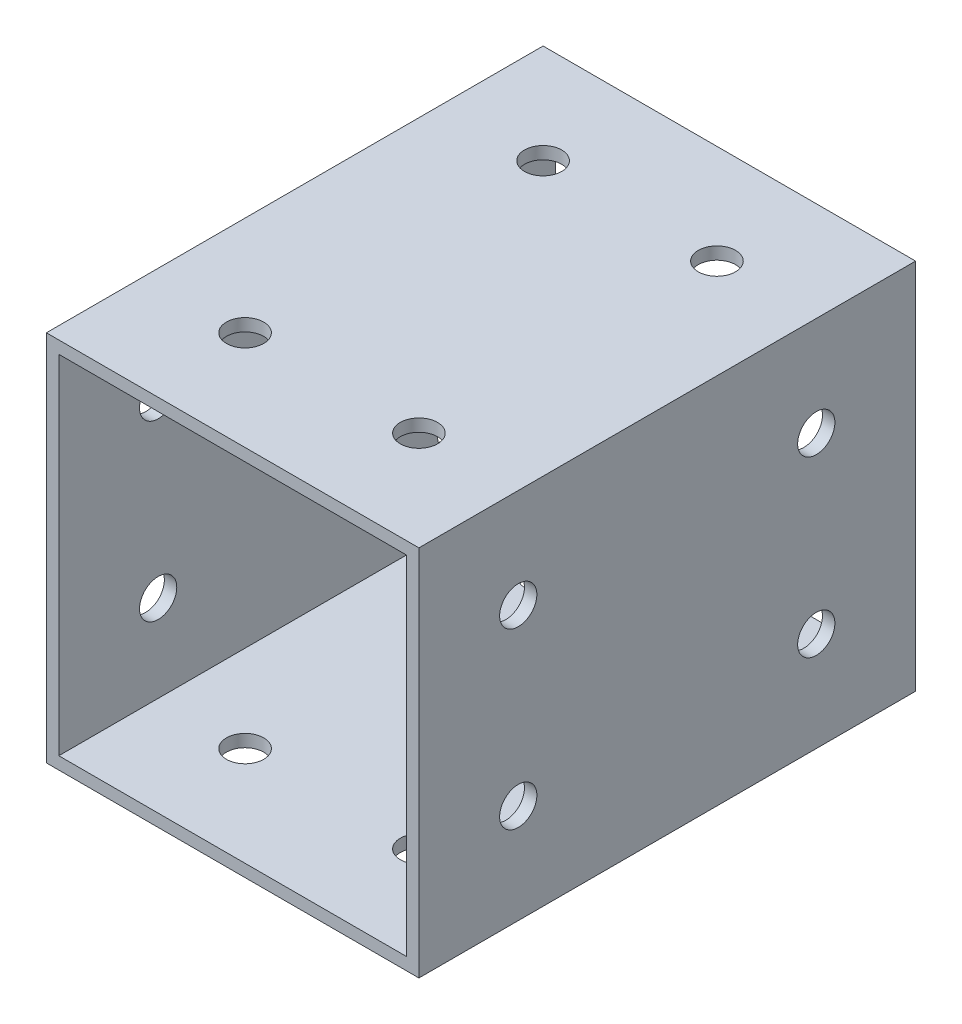
SolidWorks part; units mm, degrees
material "6061 合金"
ref_plane "Front" through (0, 0, 0) normal (0, 0, 1) x (1, 0, 0)
ref_plane "Top" through (0, 0, 0) normal (0, 1, 0) x (1, 0, 0)
ref_plane "Right" through (0, 0, 0) normal (1, 0, 0) x (0, 0, -1)
sketch "草图1" plane through (0, 0, 0) normal (0, 0, 1) x (1, 0, 0)
  line L1 (-15, -15) -> (15, -15)
  line L2 (-15, -15) -> (-15, 15)
  line L3 (-15, 15) -> (15, 15)
  line L4 (15, -15) -> (15, 15)
  line L5 (-15, -15) -> (15, 15) construction
  line L6 (-15, 15) -> (15, -15) construction
  line L7 (-14, -14) -> (14, -14)
  line L8 (-14, -14) -> (-14, 14)
  line L9 (-14, 14) -> (14, 14)
  line L10 (14, -14) -> (14, 14)
  line L11 (-14, -14) -> (14, 14) construction
  line L12 (-14, 14) -> (14, -14) construction
  point P0 (0, 0)
  point P5 (0, 0)
  dimension "D1" = 30
  dimension "D2" = 30
  dimension "D3" = 1
  dimension "D4" = 1
extrude "凸台-拉伸1" add sketch "草图1" along normal blind 40
sketch "草图2" plane through (-15, 0, 0) normal (-1, 0, 0) x (0, 0, 1)
  line L0 (8, 7) -> (32, 7) construction
  line L1 (32, 7) -> (32, -7) construction
  line L2 (32, -7) -> (8, -7) construction
  line L3 (8, -7) -> (8, 7) construction
  line L4 (40, 15) -> (40, -15) construction
  line L5 (0, 15) -> (0, -15) construction
  line L6 (40, 15) -> (0, 15) construction
  line L7 (40, -15) -> (0, -15) construction
  circle A1 centre (32, -7) radius 1.5
  circle A2 centre (8, -7) radius 1.5
  circle A3 centre (32, 7) radius 1.5
  circle A4 centre (8, 7) radius 1.5
  dimension "D1" = 3
  dimension "D2" = 3
  dimension "D7" = 3
  dimension "D8" = 3
  dimension "D3" = 8
  dimension "D4" = 8
  dimension "D5" = 8
  dimension "D6" = 8
extrude "切除-拉伸1" cut sketch "草图2" against normal through all
sketch "草图3" plane through (0, 15, 0) normal (0, 1, 0) x (1, 0, 0)
  line L0 (-7, -8) -> (7, -8) construction
  line L1 (7, -8) -> (7, -32) construction
  line L2 (7, -32) -> (-7, -32) construction
  line L3 (-7, -32) -> (-7, -8) construction
  line L4 (15, -40) -> (15, 0) construction
  line L5 (-15, -40) -> (-15, 0) construction
  line L6 (15, 0) -> (-15, 0) construction
  line L7 (15, -40) -> (-15, -40) construction
  circle A0 centre (7, -32) radius 1.5
  circle A1 centre (-7, -32) radius 1.5
  circle A2 centre (7, -8) radius 1.5
  circle A3 centre (-7, -8) radius 1.5
  dimension "D1" = 3
  dimension "D2" = 3
  dimension "D3" = 3
  dimension "D4" = 3
  dimension "D5" = 8
  dimension "D6" = 8
  dimension "D7" = 8
  dimension "D8" = 8
extrude "切除-拉伸2" cut sketch "草图3" against normal through all
